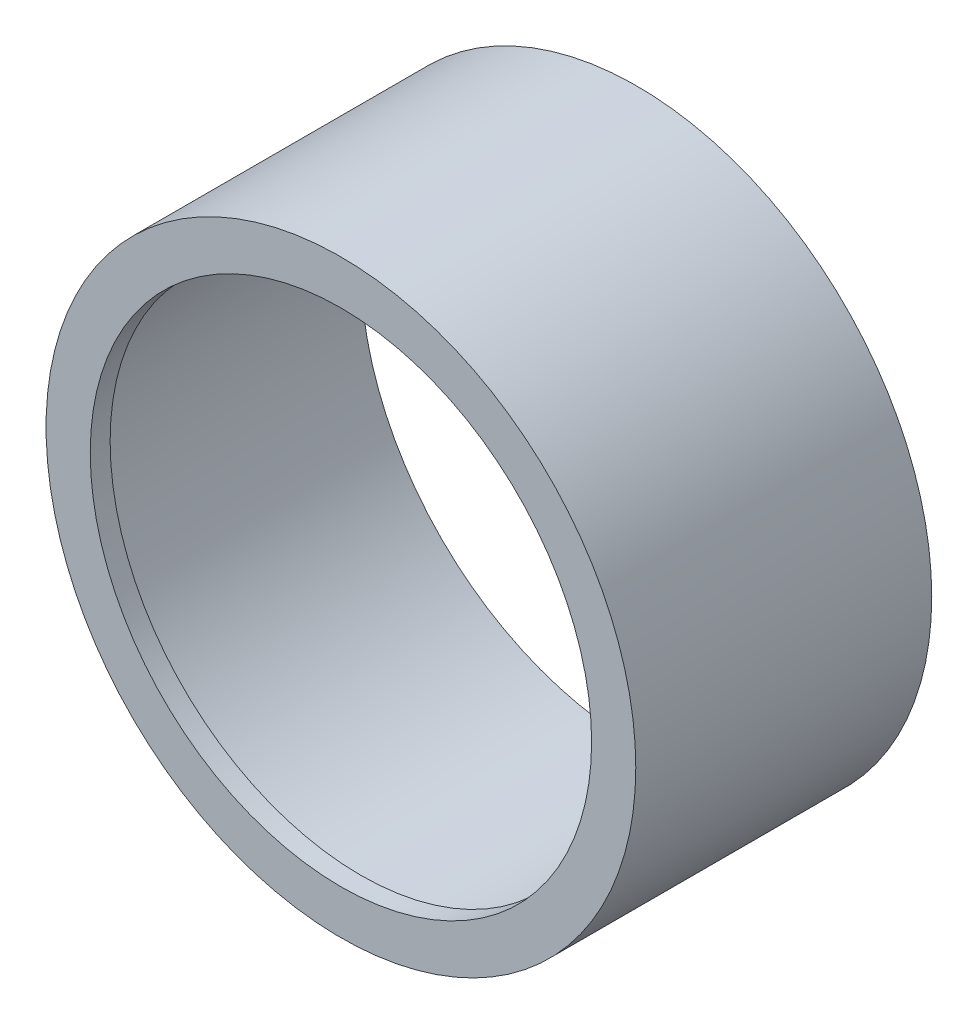
SolidWorks part; units mm, degrees
ref_plane "Front Plane" through (0, 0, 0) normal (0, 0, 1) x (1, 0, 0)
ref_plane "Top Plane" through (0, 0, 0) normal (0, 1, 0) x (1, 0, 0)
ref_plane "Right Plane" through (0, 0, 0) normal (1, 0, 0) x (0, 0, -1)
sketch "Sketch1" plane through (0, 0, 0) normal (0, 0, 1) x (1, 0, 0)
  circle A0 centre (0, 0) radius 25
  circle A1 centre (0, 0) radius 26.7
  circle A2 centre (0, 0) radius 25 construction
  dimension "D1" = 1.7
extrude "Boss-Extrude1" add sketch "Sketch1" against normal up to surface (25 mm away)
sketch "Sketch2" plane through (0, 0, 0) normal (0, 0, 1) x (1, 0, 0)
  circle A0 centre (0, 0) radius 26.7
  circle A1 centre (0, 0) radius 26.7 construction
  circle A2 centre (0, 0) radius 22.7
  dimension "D1" = 4
extrude "Boss-Extrude2" add sketch "Sketch2" along normal blind 1.8
